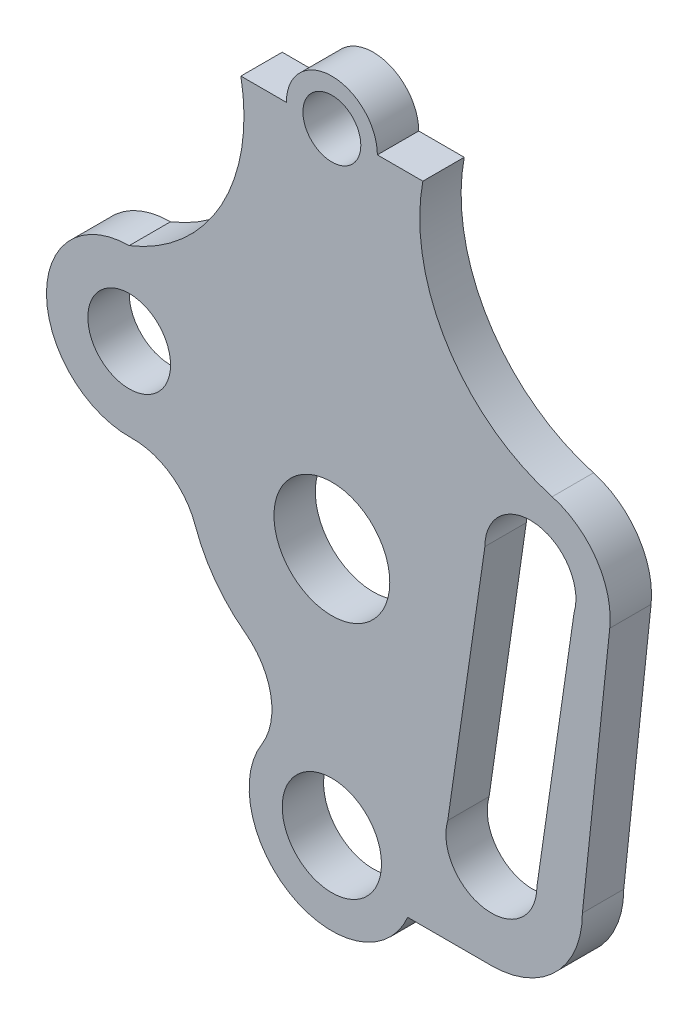
SolidWorks part; units mm, degrees
ref_plane "Front Plane" through (0, 0, 0) normal (0, 0, 1) x (1, 0, 0)
ref_plane "Top Plane" through (0, 0, 0) normal (0, 1, 0) x (1, 0, 0)
ref_plane "Right Plane" through (0, 0, 0) normal (1, 0, 0) x (0, 0, -1)
sketch "Sketch1" plane through (0, 0, 0) normal (0, 0, 1) x (1, 0, 0)
  line L0 (0, 0) -> (0, 50000) construction
  line L1 (0, 0) -> (-50000, 0) construction
  line L2 (0, 0) -> (47.5001, -56.6084) construction
  line L3 (-11, 88) -> (-22, 88)
  line L4 (11, 88) -> (22, 88)
  line L5 (67.1805, 16.9849) -> (60.5673, -45.9627)
  line L7 (37, 19) -> (27.5673, -45.9627)
  line L8 (59, 19) -> (49.5673, -45.9627)
  line L9 (18.3466, -67.9627) -> (38.5673, -67.9627)
  circle A0 centre (0, 0) radius 14
  circle A1 centre (0, -60) radius 12
  circle A2 centre (0, 88) radius 7
  arc A3 (11, 88) -> (-11, 88) centre (0, 88) ccw
  circle A4 centre (-49, 19) radius 10
  arc A5 (-22, 88) -> (-49, 39) centre (-65.2463, 79.8908) cw
  arc A6 (-49, 39) -> (-48.493, -0.9936) centre (-49, 19) ccw
  arc A7 (22, 88) -> (53.2557, 37.5561) centre (65.2463, 79.8908) ccw
  arc A10 (-33.0011, -11.6587) -> (-20.9312, -28.0515) centre (0, 0) ccw
  arc A11 (58.1538, 14.7692) -> (37, 19) centre (48, 19) ccw
  arc A12 (-48.493, -0.9936) -> (-33.0011, -11.6587) centre (-48.0874, -16.9884) cw
  arc A13 (-16.9443, -49.375) -> (-20.9312, -28.0515) centre (-30.4997, -40.875) ccw
  arc A15 (28.0215, -42.8342) -> (49.5673, -45.9627) centre (38.5673, -45.9627) ccw
  arc A17 (38.5673, -67.9627) -> (60.5673, -45.9627) centre (38.5673, -45.9627) ccw
  circle A18 centre (0, 0) radius 60 construction
  arc A19 (67.1805, 16.9849) -> (53.2557, 37.5561) centre (48, 19) ccw
  arc A20 (35, 0) -> (34.793, 3.8007) centre (0, 0) ccw
  arc A21 (-16.9443, -49.375) -> (18.3466, -67.9627) centre (0, -60) ccw
  point P31 (38.5673, -67.9627)
  point P38 (19.5607, -64.1689)
  point P46 (-11, -54.3936)
  point P47 (-18.8165, -53.2221)
  point P48 (-22, -27.5339)
  point P50 (16.7815, -70.8803)
  point P51 (13.9377, -74.3437)
  dimension "D1" = 28
  dimension "D3" = 24
  dimension "D4" = 14
  dimension "D6" = 22
  dimension "D7" = 20
  dimension "D11" = 40
  dimension "D12" = 44
  dimension "D14" = 70
  dimension "D15" = 16
  dimension "D16" = 16
  dimension "D17" = 22
  dimension "D20" = 40
  dimension "D2" = 22
  dimension "D22" = 44
  dimension "D5" = 88
  dimension "D8" = 69
  dimension "D9" = 49
  dimension "D10" = 60
  dimension "D13" = 22
  dimension "D18" = 48
  dimension "D19" = 19
extrude "Boss-Extrude1" add sketch "Sketch1" along normal mid plane 10 contours A13 A21 L9 A17 L5 A19 A7 L4 A3 L3 A5 A6 A12 A10 A0 A1 A2 A4 A15 L7 A11 L8
